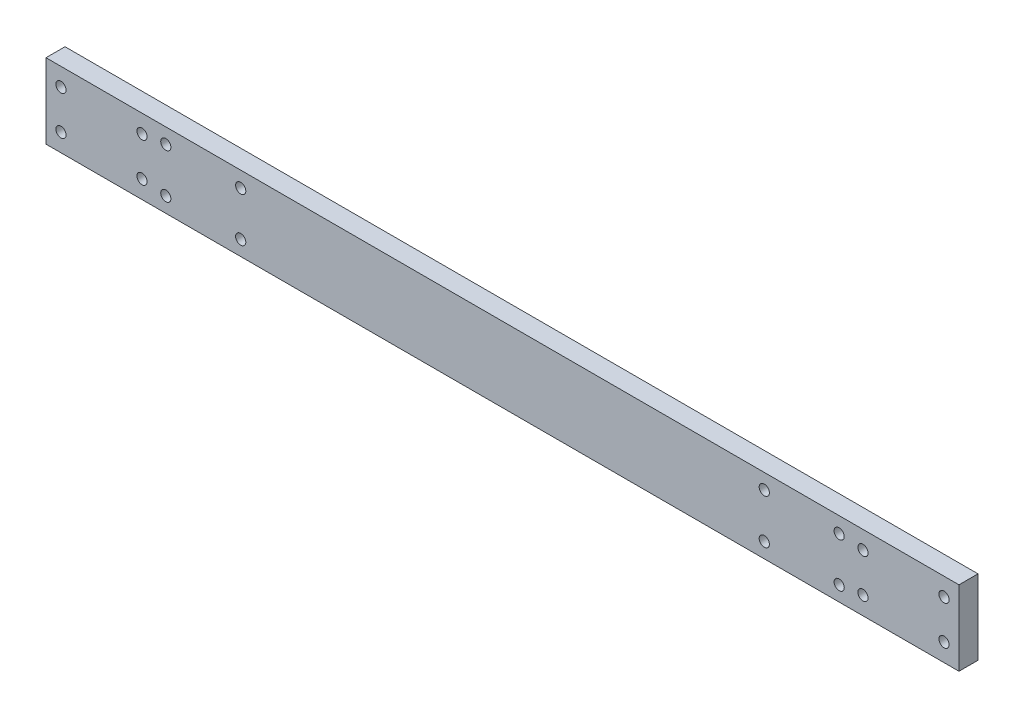
SolidWorks part; units mm, degrees
material "Balsa"
ref_plane "Front Plane" through (0, 0, 0) normal (0, 0, 1) x (1, 0, 0)
ref_plane "Top Plane" through (0, 0, 0) normal (0, 1, 0) x (1, 0, 0)
ref_plane "Right Plane" through (0, 0, 0) normal (1, 0, 0) x (0, 0, -1)
sketch "Sketch1" plane through (0, 0, 0) normal (0, 0, 1) x (1, 0, 0)
  line L1 (-40.7762, 235.9236) -> (264.0238, 235.9236)
  line L2 (-40.7762, 235.9236) -> (-40.7762, 210.9236)
  line L3 (-40.7762, 210.9236) -> (264.0238, 210.9236)
  line L4 (-40.7762, 235.9236) -> (-40.7762, -68.8764)
  line L5 (-40.7762, -68.8764) -> (264.0238, -68.8764)
  line L6 (264.0238, -68.8764) -> (264.0238, 235.9236)
  line L7 (264.0238, 235.9236) -> (-40.7762, 235.9236)
  line L11 (264.0238, 235.9236) -> (-40.7762, 235.9236)
  line L12 (264.0238, 235.9236) -> (264.0238, 210.9236)
  dimension "D1" = 0
extrude "Boss-Extrude1" add sketch "Sketch1" along normal blind 6.35 contours L12 L1 L2 L3
sketch "Sketch2" plane through (0, 0, 6.35) normal (0, 0, 1) x (1, 0, 0)
  circle A0 centre (-35.7762, 229.9236) radius 1.7 construction
  circle A1 centre (-35.7762, 216.9236) radius 1.7 construction
  circle A2 centre (-35.7762, 229.9236) radius 1.7
  circle A3 centre (-35.7762, 216.9236) radius 1.7
  circle A4 centre (-8.7262, 229.9236) radius 1.7 construction
  circle A5 centre (-8.7262, 216.9236) radius 1.7 construction
  circle A6 centre (-8.7262, 229.9236) radius 1.7
  circle A7 centre (-8.7262, 216.9236) radius 1.7
  circle A8 centre (-0.7762, 230.865) radius 1.7 construction
  circle A9 centre (-0.7762, 215.9822) radius 1.7 construction
  circle A10 centre (-0.7762, 230.865) radius 1.7
  circle A11 centre (-0.7762, 215.9822) radius 1.7
  circle A12 centre (24.2238, 230.7166) radius 1.7 construction
  circle A13 centre (24.2238, 215.9236) radius 1.7 construction
  circle A14 centre (24.2238, 230.7166) radius 1.7
  circle A15 centre (24.2238, 215.9236) radius 1.7
  circle A16 centre (199.0238, 215.9822) radius 1.7 construction
  circle A17 centre (199.0238, 230.865) radius 1.7 construction
  circle A18 centre (199.0238, 215.9822) radius 1.7
  circle A19 centre (199.0238, 230.865) radius 1.7
  circle A20 centre (224.0238, 230.7166) radius 1.7 construction
  circle A21 centre (224.0238, 215.9236) radius 1.7 construction
  circle A22 centre (224.0238, 230.7166) radius 1.7
  circle A23 centre (224.0238, 215.9236) radius 1.7
  circle A24 centre (231.9738, 229.9236) radius 1.7 construction
  circle A25 centre (231.9738, 216.9236) radius 1.7 construction
  circle A26 centre (231.9738, 229.9236) radius 1.7
  circle A27 centre (231.9738, 216.9236) radius 1.7
  circle A28 centre (259.0238, 216.9236) radius 1.7 construction
  circle A29 centre (259.0238, 229.9236) radius 1.7 construction
  circle A30 centre (259.0238, 216.9236) radius 1.7
  circle A31 centre (259.0238, 229.9236) radius 1.7
extrude "Cut-Extrude1" cut sketch "Sketch2" against normal blind 22
